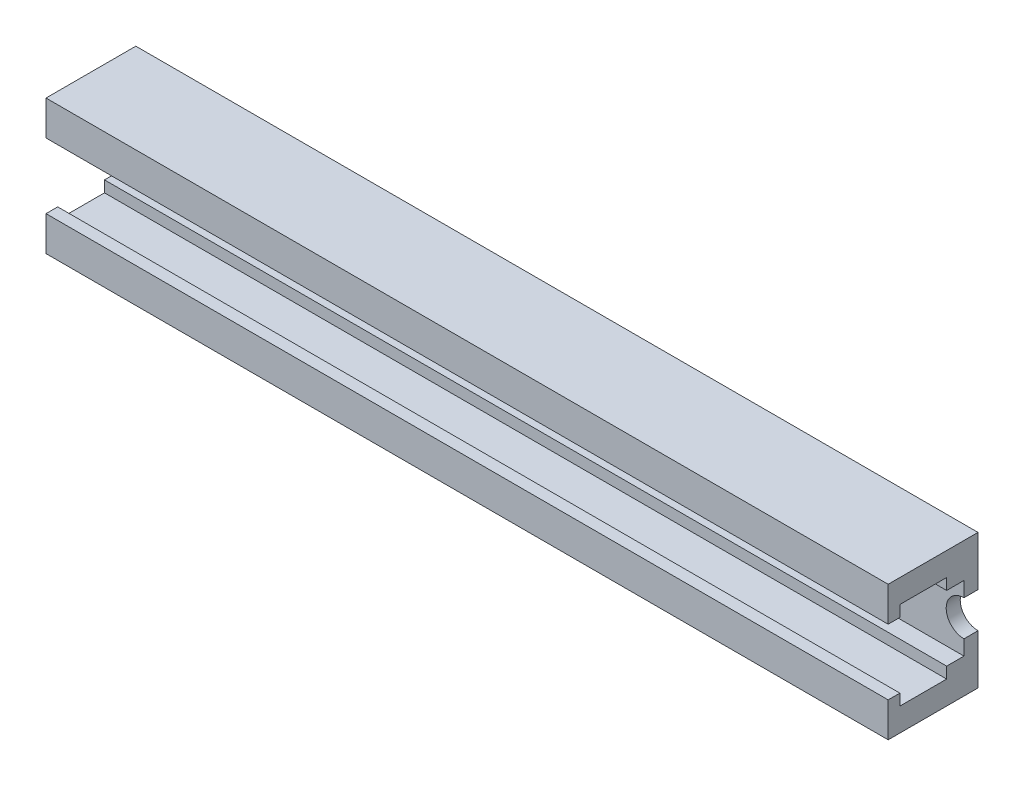
SolidWorks part; units mm, degrees
ref_plane "Front" through (0, 0, 0) normal (0, 0, 1) x (1, 0, 0)
ref_plane "Top" through (0, 0, 0) normal (0, 1, 0) x (1, 0, 0)
ref_plane "Right" through (0, 0, 0) normal (1, 0, 0) x (0, 0, -1)
sketch "Sketch1" plane through (0, 0, 0) normal (1, 0, 0) x (0, 0, -1)
  line L1 (0, 9.144) -> (-12.192, 9.144)
  line L2 (0, 9.144) -> (0, -9.144)
  line L3 (0, -9.144) -> (-12.192, -9.144)
  line L4 (-12.192, 9.144) -> (-12.192, -9.144)
  point P4 (0, 0)
  dimension "D1" = 18.288
  dimension "D2" = 12.192
sketch "Sketch2" plane through (0, 0, 0) normal (1, 0, 0) x (0, 0, -1)
  line L0 (0, 9.144) -> (-12.192, 9.144)
  line L1 (-12.192, 9.144) -> (-12.192, 4.445)
  line L2 (-12.192, 9.144) -> (-12.192, -9.144) construction
  line L3 (-12.192, 4.445) -> (-10.6045, 4.445)
  line L4 (-10.6045, 4.445) -> (-10.6045, 5.969)
  line L5 (-10.6045, 5.969) -> (-4.2545, 5.969)
  line L6 (-4.2545, 5.969) -> (-4.2545, 4.445)
  line L7 (-4.2545, 4.445) -> (-1.905, 4.445)
  line L8 (-1.905, 4.445) -> (-1.905, -4.445)
  line L9 (-1.905, -4.445) -> (-4.2545, -4.445)
  line L10 (-4.2545, -4.445) -> (-4.2545, -5.969)
  line L11 (-4.2545, -5.969) -> (-10.6045, -5.969)
  line L12 (-10.6045, -5.969) -> (-10.6045, -4.445)
  line L13 (-10.6045, -4.445) -> (-12.192, -4.445)
  line L14 (-12.192, -4.445) -> (-12.192, -9.144)
  line L15 (-12.192, -9.144) -> (0, -9.144)
  line L16 (0, -9.144) -> (0, 9.144)
  line L17 (0, 0) -> (-19.0377, 0) construction
  point P25 (-1.905, 0)
  dimension "D1" = 1.905
  dimension "D2" = 8.89
  dimension "D3" = 3.175
  dimension "D4" = 6.35
  dimension "D5" = 8.89
  dimension "D6" = 1.5875
extrude "Boss-Extrude1" add sketch "Sketch2" along normal mid plane 457.2
sketch "Sketch3" plane through (0, 0, 1.905) normal (0, 0, 1) x (1, 0, 0)
  line L0 (0, 0) -> (38.1, 0) construction
  line L1 (0, 0) -> (0, 27.0833) construction
  circle A0 centre (38.1, 0) radius 2.413
  dimension "D2" = 4.826
  dimension "D1" = 76.2
extrude "Cut-Extrude1" cut sketch "Sketch3" against normal up to surface (1.905 mm away) up to face at (0, 0, 0)
pattern_linear "LPattern1" count 3 spacing 76.2 along (1, 0, 0) of "Cut-Extrude1"
other "SurfaceCut1"
mirror "Mirror1" about plane through (0, 0, 0) normal (1, 0, 0) of bodies 112
sketch "Sketch4" plane through (228.6, 0, 0) normal (1, 0, 0) x (0, 0, -1)
  line L1 (-17.1118, 12.0015) -> (5.6929, 12.0015)
  line L2 (-17.1118, 12.0015) -> (-17.1118, -12.7358)
  line L3 (-17.1118, -12.7358) -> (5.6929, -12.7358)
  line L4 (5.6929, 12.0015) -> (5.6929, -12.7358)
extrude "Cut-Extrude2" cut sketch "Sketch4" against normal blind 342.9
